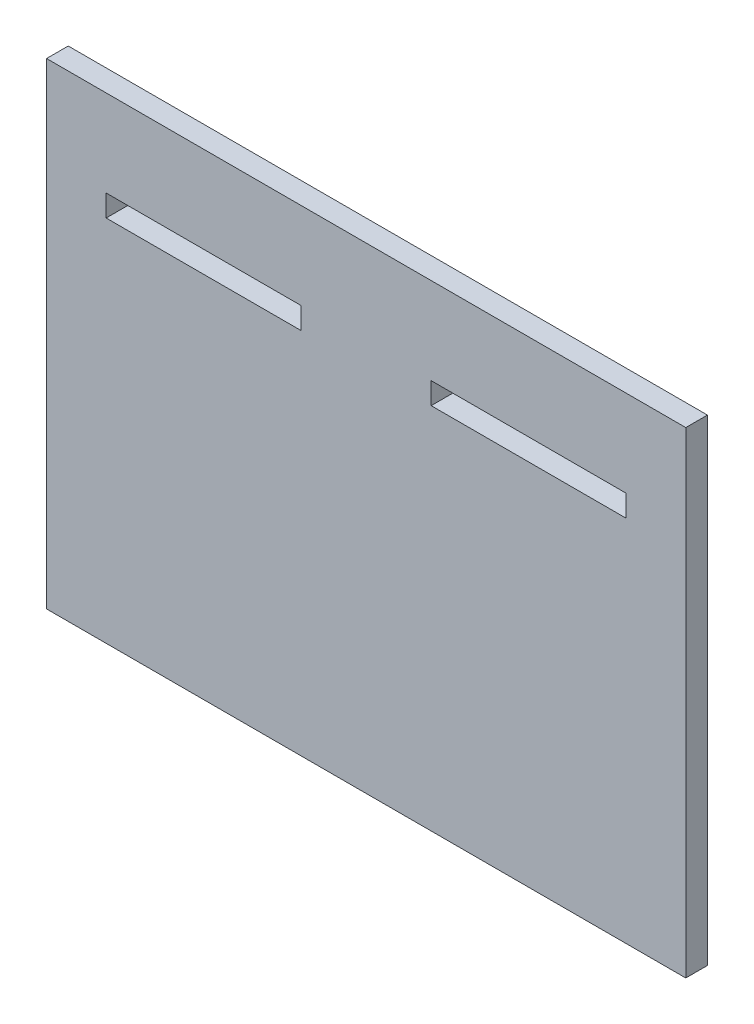
SolidWorks part; units mm, degrees
ref_plane "Plan de face" through (0, 0, 0) normal (0, 0, 1) x (1, 0, 0)
ref_plane "Plan de dessus" through (0, 0, 0) normal (0, 1, 0) x (1, 0, 0)
ref_plane "Plan de droite" through (0, 0, 0) normal (1, 0, 0) x (0, 0, -1)
sketch "Esquisse1" plane through (0, 0, 0) normal (0, 0, 1) x (1, 0, 0)
  line L0 (0, 220) -> (295, 220)
  line L1 (0, 0) -> (295, 0)
  line L2 (0, 0) -> (0, 220)
  line L3 (0, 180) -> (295, 180) construction
  line L4 (295, 0) -> (295, 220)
  line L5 (295, 175) -> (0, 175) construction
  line L6 (0, 170) -> (295, 170) construction
  line L7 (177.5, 170) -> (117.5, 170) construction
  line L8 (27.5, 180) -> (117.5, 180)
  line L9 (27.5, 180) -> (27.5, 170)
  line L10 (27.5, 170) -> (117.5, 170)
  line L11 (117.5, 180) -> (117.5, 170)
  line L12 (177.5, 180) -> (267.5, 180)
  line L13 (177.5, 180) -> (177.5, 170)
  line L14 (177.5, 170) -> (267.5, 170)
  line L15 (267.5, 180) -> (267.5, 170)
  line L16 (147.5, 170) -> (147.5, 180) construction
  dimension "D1" = 10
  dimension "D2" = 5
  dimension "D3" = 40
  dimension "D4" = 220
  dimension "D5" = 295
  dimension "D6" = 90
  dimension "D7" = 60
  dimension "D8" = 90
extrude "Boss.-Extru.1" add sketch "Esquisse1" along normal blind 10
